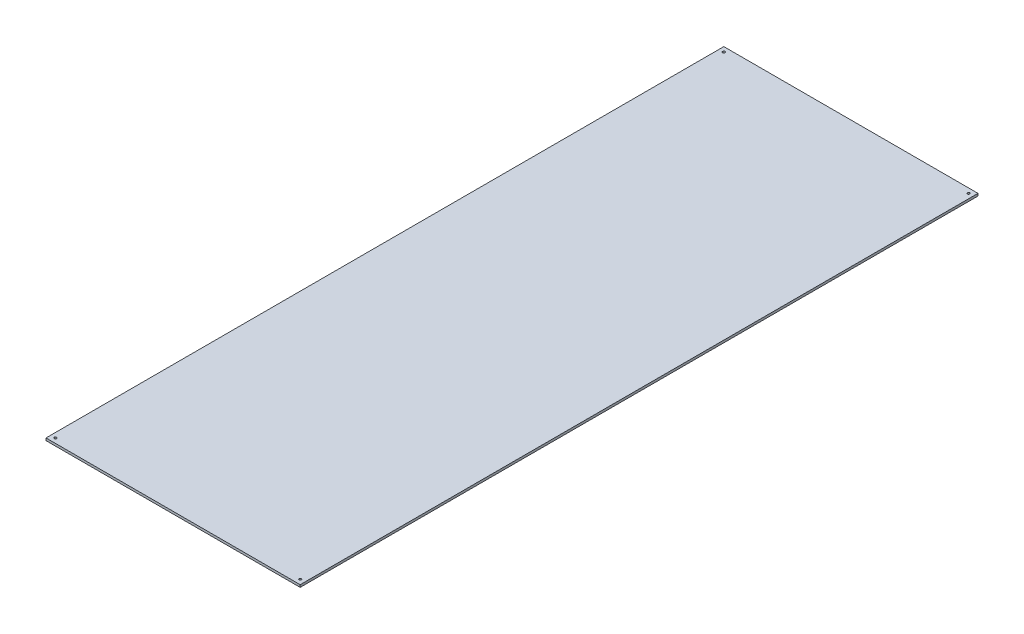
SolidWorks part; units mm, degrees
ref_plane "Front Plane" through (0, 0, 0) normal (0, 0, 1) x (1, 0, 0)
ref_plane "Top Plane" through (0, 0, 0) normal (0, 1, 0) x (1, 0, 0)
ref_plane "Right Plane" through (0, 0, 0) normal (1, 0, 0) x (0, 0, -1)
sketch "Sketch1" plane through (0, 0, 0) normal (0, 1, 0) x (1, 0, 0)
  line L1 (-342.9, -914.4) -> (342.9, -914.4)
  line L2 (-342.9, -914.4) -> (-342.9, 914.4)
  line L3 (-342.9, 914.4) -> (342.9, 914.4)
  line L4 (342.9, -914.4) -> (342.9, 914.4)
  line L5 (-342.9, -914.4) -> (342.9, 914.4) construction
  line L6 (-342.9, 914.4) -> (342.9, -914.4) construction
  point P0 (0, 0)
  dimension "D1" = 685.8
  dimension "D2" = 1828.8
extrude "Boss-Extrude1" add sketch "Sketch1" along normal blind 6.35
sketch "Sketch2" plane through (0, 6.35, 0) normal (0, 1, 0) x (1, 0, 0)
  line L0 (342.9, -914.4) -> (342.9, 914.4) construction
  line L1 (342.9, 914.4) -> (-342.9, 914.4) construction
  circle A4 centre (-330.2, -901.7) radius 2.6035 construction
  circle A5 centre (330.2, -901.7) radius 2.6035 construction
  circle A6 centre (330.2, 901.7) radius 2.6035 construction
  circle A7 centre (-330.2, 901.7) radius 2.6035 construction
  circle A8 centre (330.2, -901.7) radius 3.175
  circle A9 centre (-330.2, -901.7) radius 3.175
  circle A10 centre (330.2, 901.7) radius 3.175
  circle A11 centre (-330.2, 901.7) radius 3.175
  dimension "D1" = 5.207
  dimension "D6" = 6.35
  dimension "D7" = 6.35
  dimension "D8" = 6.35
  dimension "D9" = 6.35
  dimension "D2" = 12.7
  dimension "D3" = 673.1
  dimension "D4" = 12.7
  dimension "D5" = 1816.1
extrude "Cut-Extrude1" cut sketch "Sketch2" against normal through all
